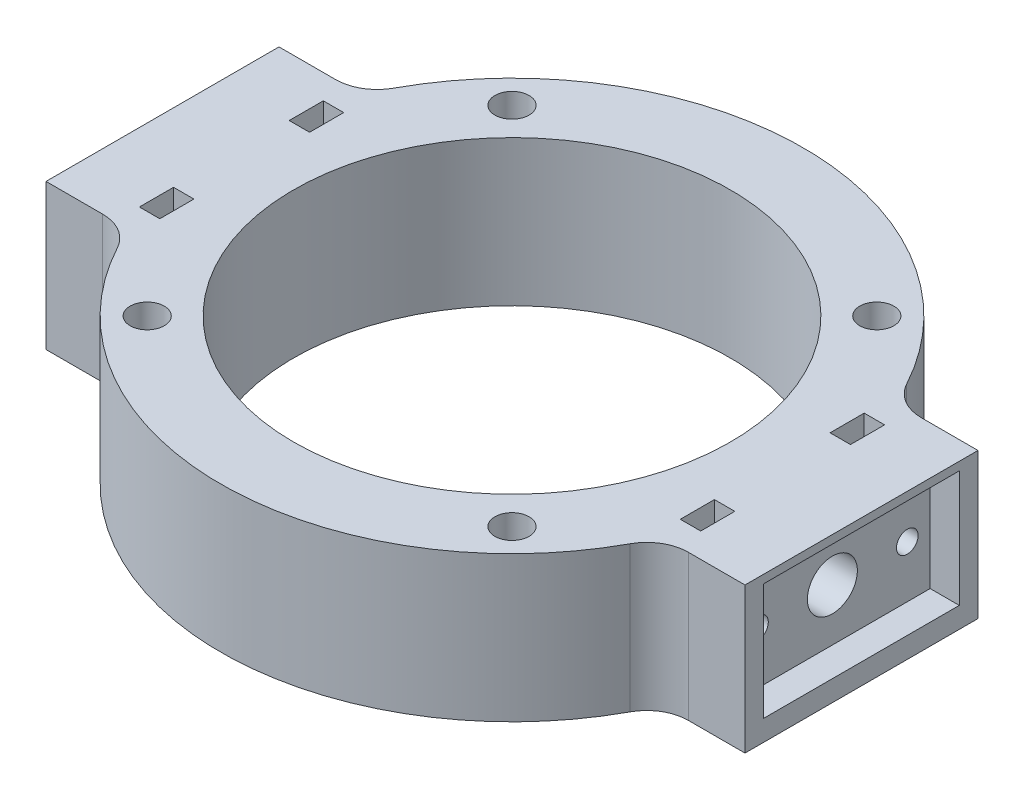
SolidWorks part; units mm, degrees
material "ABS"
ref_plane "Ön Düzlem" through (0, 0, 0) normal (0, 0, 1) x (1, 0, 0)
ref_plane "Üst Düzlem" through (0, 0, 0) normal (0, 1, 0) x (1, 0, 0)
ref_plane "Sağ Düzlem" through (0, 0, 0) normal (1, 0, 0) x (0, 0, -1)
sketch "Çizim1" plane through (0, 0, 0) normal (0, 1, 0) x (1, 0, 0)
  line L0 (-64.1561, 28) -> (-84, 28)
  line L1 (84, 28) -> (64.1561, 28)
  line L2 (84, -28) -> (64.1561, -28)
  line L3 (-84, 28) -> (-84, -28)
  line L4 (84, 28) -> (84, -28)
  line L5 (-64.1561, -28) -> (-84, -28)
  arc A0 (64.1561, 28) -> (-64.1561, 28) centre (0, 0) ccw
  circle A1 centre (0, 0) radius 52.5
  arc A2 (-64.1561, -28) -> (64.1561, -28) centre (0, 0) ccw
  point P7 (0, 0)
  dimension "D1" = 105
  dimension "D2" = 140
  dimension "D5" = 168
extrude "Yükseklik-Ekstrüzyon1" add sketch "Çizim1" along normal blind 35
sketch "Çizim2" plane through (84, 0, 0) normal (1, 0, 0) x (0, 0, -1)
  line L0 (28, 35) -> (28, 0) construction
  line L1 (-28, 35) -> (28, 35) construction
  circle A0 centre (0, 17.5) radius 6.01
  dimension "D1" = 12.02
  dimension "D2" = 28
  dimension "D3" = 17.5
extrude "Kes-Ekstrüzyon1" cut sketch "Çizim2" against normal blind 27.24
ref_plane "Düzlem1" through (0, 0, 0) normal (1, 0, 0) x (0, 0, -1)
mirror "Aynalama1" about plane through (0, 0, 0) normal (1, 0, 0) of "Kes-Ekstrüzyon1"
sketch "Çizim3" plane through (84, 0, 0) normal (1, 0, 0) x (0, 0, -1)
  line L1 (23.5, 5) -> (-23.5, 5)
  line L2 (23.5, 5) -> (23.5, 33)
  line L3 (23.5, 33) -> (-23.5, 33)
  line L4 (-23.5, 5) -> (-23.5, 33)
  line L5 (23.5, 5) -> (-23.5, 33) construction
  line L6 (23.5, 33) -> (-23.5, 5) construction
  point P0 (0, 19)
  point P8 (0, 17.5)
  dimension "D3" = 1.5
  dimension "D1" = 47
  dimension "D2" = 28
extrude "Kes-Ekstrüzyon2" cut sketch "Çizim3" against normal blind 7
mirror "Aynalama2" about plane through (0, 0, 0) normal (1, 0, 0) of "Kes-Ekstrüzyon2"
sketch "Çizim4" plane through (77, 0, 0) normal (1, 0, 0) x (0, 0, -1)
  circle A0 centre (18, 17.5) radius 2.6
  circle A1 centre (-18, 17.5) radius 2.6
  dimension "D2" = 5.2
extrude "Kes-Ekstrüzyon3" cut sketch "Çizim4" against normal blind 20
mirror "Aynalama3" about plane through (0, 0, 0) normal (1, 0, 0) of "Kes-Ekstrüzyon3"
sketch "Çizim5" plane through (0, 35, 0) normal (0, 1, 0) x (1, 0, 0)
  line L0 (-131.3146, 0) -> (126.6936, 0) construction
  line L9 (-84, 28) -> (-84, -28)
  line L12 (0, -84.9615) -> (0, 87.9995) construction
  line L13 (67.45, 13.9) -> (62.55, 13.9)
  line L14 (62.55, 22.1) -> (62.55, 13.9)
  line L15 (67.45, 22.1) -> (62.55, 22.1)
  line L16 (67.45, 22.1) -> (67.45, 13.9)
  line L17 (67.45, -22.1) -> (67.45, -13.9)
  line L18 (67.45, -22.1) -> (62.55, -22.1)
  line L19 (62.55, -22.1) -> (62.55, -13.9)
  line L20 (67.45, -13.9) -> (62.55, -13.9)
  line L21 (-65, 28) -> (-65, -28)
  dimension "D1" = 19
ref_plane "Düzlem2" through (-65, 0, 0) normal (-1, 0, 0) x (0, 0, 1)
sketch "Çizim6" plane through (-65, 0, 0) normal (-1, 0, 0) x (0, 0, 1)
  line L0 (-22.1, 35) -> (-13.9, 35)
  line L2 (-18, 12.7657) -> (-13.9, 15.1329)
  line L3 (-13.9, 15.1329) -> (-13.9, 35)
  line L6 (-22.1, 35) -> (-22.1, 15.1329)
  line L7 (-22.1, 15.1329) -> (-18, 12.7657)
  line L8 (18, 12.7657) -> (22.1, 15.1329)
  line L9 (22.1, 15.1329) -> (22.1, 35)
  line L12 (13.9, 35) -> (13.9, 15.1329)
  line L13 (13.9, 15.1329) -> (18, 12.7657)
  line L14 (13.9, 35) -> (22.1, 35)
  line L15 (15.95, 21.0507) -> (13.9, 19.8671) [skipped]
  line L16 (22.1, 19.8671) -> (20.05, 21.0507) [skipped]
  line L17 (-20.05, 21.0507) -> (-22.1, 19.8671) [skipped]
  line L18 (-13.9, 19.8671) -> (-15.95, 21.0507) [skipped]
  dimension "D1" = 8.2
  dimension "D2" = 8.2
extrude "Kes-Ekstrüzyon4" cut sketch "Çizim6" against normal blind 2.45 and the other way blind 2.45
mirror "Aynalama4" about plane through (0, 0, 0) normal (1, 0, 0) of "Kes-Ekstrüzyon4"
sketch "Çizim7" plane through (0, 35, 0) normal (0, 1, 0) x (1, 0, 0)
  circle A1 centre (43.8406, -43.8406) radius 4.1
  circle A3 centre (-43.8406, -43.8406) radius 4.1
  circle A4 centre (-43.8406, 43.8406) radius 4.1
  circle A5 centre (43.8406, 43.8406) radius 4.1
  point P16 (0, 0)
  dimension "D1" = 4
  dimension "D2" = 8.2
extrude "Kes-Ekstrüzyon5" cut sketch "Çizim7" against normal through all
fillet "Radyus1" radius 10 4 edges at (-64.1561, 17.5, -28) (-64.1561, 17.5, 28) (64.1561, 17.5, -28) (64.1561, 17.5, 28)
ref_plane "Düzlem3" through (0, 17.5, 0) normal (0, 1, 0) x (1, 0, 0)
